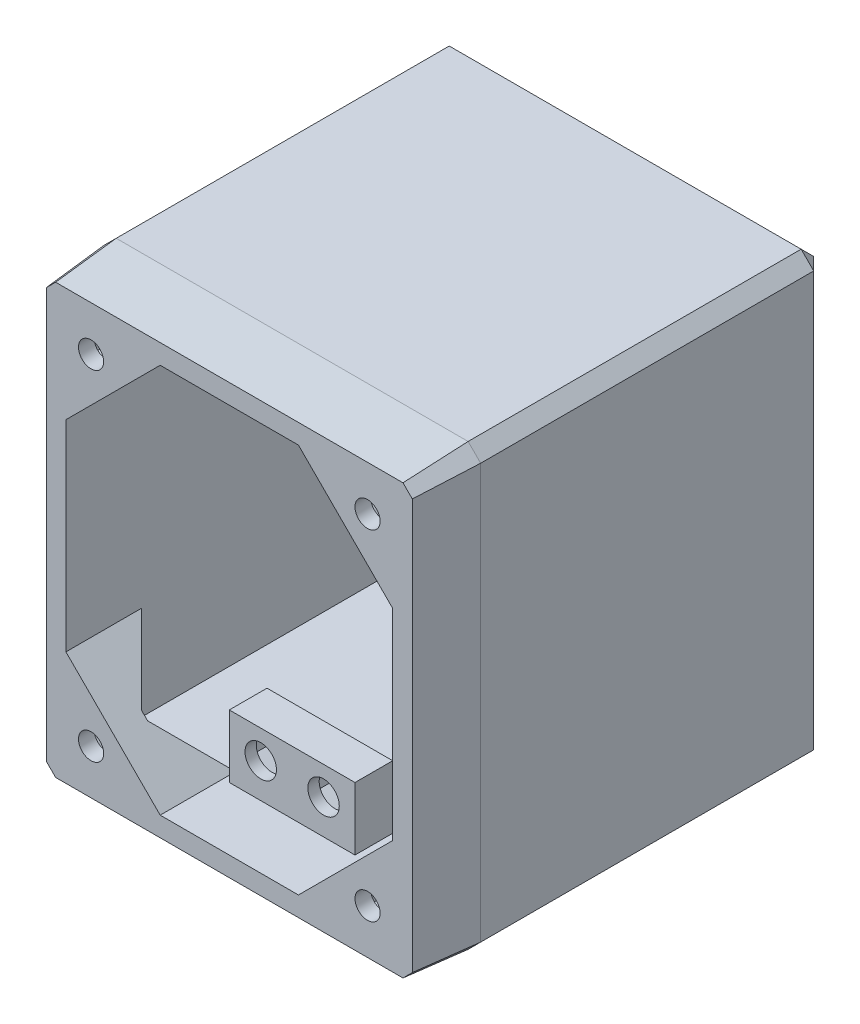
SolidWorks part; units mm, degrees
ref_plane "Ebene vorne" through (0, 0, 0) normal (0, 0, 1) x (1, 0, 0)
ref_plane "Ebene oben" through (0, 0, 0) normal (0, 1, 0) x (1, 0, 0)
ref_plane "Ebene rechts" through (0, 0, 0) normal (1, 0, 0) x (0, 0, -1)
sketch "Skizze1" plane through (0, 0, 0) normal (0, 0, 1) x (1, 0, 0)
  line L1 (0, 0) -> (60, 0)
  line L2 (0, 0) -> (0, 70)
  line L3 (0, 70) -> (60, 70)
  line L4 (60, 0) -> (60, 70)
  dimension "D1" = 60
  dimension "D2" = 70
extrude "Grundkörper" add sketch "Skizze1" along normal blind 65
chamfer "Fase2" distance 2 angle 45 7 edges at (0, 0, 32.5) (60, 0, 32.5) (60, 70, 32.5) (0, 70, 32.5) (0, 35, 0) (30, 70, 0) (60, 35, 0)
shell "Wandung1" thickness 4
sketch "Skizze2" plane through (0, 4, 0) normal (0, 1, 0) x (1, 0, 0)
  line L5 (30, -65) -> (30, -4) construction
  line L6 (4, -65) -> (56, -65) construction
  line L7 (4, -4) -> (56, -4) construction
  line L12 (40, -55) -> (20, -55)
  line L13 (20, -55) -> (20, -49)
  line L14 (20, -49) -> (40, -49)
  line L15 (58, -65) -> (2, -65) construction
  line L16 (40, -55) -> (40, -49)
  point P13 (30, -49)
  point P14 (30, -55)
  dimension "D1" = 10
  dimension "D2" = 6
  dimension "D3" = 20
extrude "Aufsatz-Linear austragen1" add sketch "Skizze2" along normal blind 10 contours L14 L16 L12 L13
ref_plane "Ebene1" through (0, 35, 0) normal (0, -1, 0) x (-1, 0, 0)
mirror "Spiegeln1" about plane through (0, 35, 0) normal (0, -1, 0) of "Aufsatz-Linear austragen1"
sketch "Skizze3" plane through (0, 0, 55) normal (0, 0, 1) x (1, 0, 0)
  line L0 (40, 14) -> (40, 4) construction
  line L2 (40, 4) -> (20, 4) construction
  line L3 (4, 4) -> (56, 4) construction
  line L4 (-28.6825, 35) -> (28.6825, 35) construction
  circle A0 centre (25, 9.5) radius 2.5
  circle A1 centre (35, 9.5) radius 2.5
  circle A2 centre (35, 60.5) radius 2.5
  circle A3 centre (25, 60.5) radius 2.5
  dimension "D3" = 5
  dimension "D4" = 5
  dimension "D1" = 10
  dimension "D2" = 5
  dimension "D5" = 5.5
  dimension "D6" = 5.5
extrude "Bohrungen Servo" cut sketch "Skizze3" against normal up to next
sketch "Skizze5" plane through (0, 0, 49) normal (0, 0, -1) x (-1, 0, 0)
  line L0 (-28.6825, 35) -> (28.6825, 35) construction
  line L1 (-34.9751, 13.5414) -> (-38.4875, 11.5423)
  line L2 (-38.4875, 11.5423) -> (-38.5124, 7.5009)
  line L3 (-38.5124, 7.5009) -> (-35.0249, 5.4586)
  line L4 (-35.0249, 5.4586) -> (-31.5125, 7.4577)
  line L5 (-31.5125, 7.4577) -> (-31.4876, 11.4991)
  line L6 (-31.4876, 11.4991) -> (-34.9751, 13.5414)
  line L7 (-31.4876, 58.5009) -> (-34.9751, 56.4586)
  line L8 (-31.5125, 62.5423) -> (-31.4876, 58.5009)
  line L9 (-35.0249, 64.5414) -> (-31.5125, 62.5423)
  line L10 (-38.5124, 62.4991) -> (-35.0249, 64.5414)
  line L11 (-38.4875, 58.4577) -> (-38.5124, 62.4991)
  line L12 (-34.9751, 56.4586) -> (-38.4875, 58.4577)
  line L13 (-30, 0) -> (-30, 70) construction
  line L14 (-2, 0) -> (-58, 0) construction
  line L15 (-58, 70) -> (-2, 70) construction
  line L16 (-28.4875, 62.5423) -> (-28.5124, 58.5009)
  line L17 (-24.9751, 64.5414) -> (-28.4875, 62.5423)
  line L18 (-21.4876, 62.4991) -> (-24.9751, 64.5414)
  line L19 (-21.5125, 58.4577) -> (-21.4876, 62.4991)
  line L20 (-25.0249, 56.4586) -> (-21.5125, 58.4577)
  line L21 (-28.5124, 58.5009) -> (-25.0249, 56.4586)
  line L22 (-28.5124, 11.4991) -> (-25.0249, 13.5414)
  line L23 (-25.0249, 13.5414) -> (-21.5125, 11.5423)
  line L24 (-21.5125, 11.5423) -> (-21.4876, 7.5009)
  line L25 (-21.4876, 7.5009) -> (-24.9751, 5.4586)
  line L26 (-24.9751, 5.4586) -> (-28.4875, 7.4577)
  line L27 (-28.4875, 7.4577) -> (-28.5124, 11.4991)
  circle A0 centre (-35, 9.5) radius 3.5 construction
  circle A1 centre (-35, 9.5) radius 2.5
  circle A2 centre (-25, 9.5) radius 2
  circle A3 centre (-25, 60.5) radius 2.5
  circle A4 centre (-35, 60.5) radius 2.5
  dimension "D2" = 4
  dimension "D1" = 7
extrude "Sechskant" cut sketch "Skizze5" against normal blind 4.2
sketch "Skizze7" plane through (0, 0, 65) normal (0, 0, 1) x (1, 0, 0)
  line L0 (56, 4) -> (41, 4)
  line L1 (4, 4) -> (56, 4) construction
  line L2 (41, 4) -> (56, 19)
  line L3 (56, 4) -> (56, 66) construction
  line L4 (56, 19) -> (56, 4)
  line L5 (30, 4) -> (30, 66) construction
  line L6 (40, 4) -> (20, 4) construction
  line L7 (56, 66) -> (4, 66) construction
  line L8 (19, 4) -> (4, 19)
  line L9 (4, 4) -> (19, 4)
  line L10 (4, 19) -> (4, 4)
  line L11 (-28.6825, 35) -> (28.6825, 35) construction
  line L12 (4, 66) -> (19, 66)
  line L13 (4, 51) -> (4, 66)
  line L14 (19, 66) -> (4, 51)
  line L15 (41, 66) -> (56, 51)
  line L16 (56, 66) -> (41, 66)
  line L17 (56, 51) -> (56, 66)
  dimension "D1" = 15
  dimension "D2" = 15
extrude "Ausparungen" add sketch "Skizze7" against normal blind 5
chamfer "Fase3" distance 7 angle 45 8 edges at (56, 58.5, 60) (48.5, 66, 60) (56, 11.5, 60) (48.5, 4, 60) (11.5, 66, 60) (4, 58.5, 60) (11.5, 4, 60) (4, 11.5, 60)
sketch "Skizze8" plane through (0, 0, 65) normal (0, 0, 1) x (1, 0, 0)
  line L0 (58, 0) -> (58, 70) construction
  line L1 (60, 2) -> (0, 2) construction
  line L2 (0, 2) -> (2, 0) construction
  line L3 (2, 0) -> (2, 70) construction
  line L4 (30, 0) -> (30, 70) construction
  line L5 (2, 0) -> (58, 0) construction
  line L6 (58, 70) -> (2, 70) construction
  line L7 (-28.6825, 35) -> (28.6825, 35) construction
  circle A0 centre (52, 8) radius 2
  circle A1 centre (8, 8) radius 2
  circle A2 centre (8, 62) radius 2
  circle A3 centre (52, 62) radius 2
  dimension "D1" = 4
  dimension "D2" = 6
  dimension "D3" = 6
extrude "BohrungenHalterung" cut sketch "Skizze8" against normal up to next
ref_plane "Ebene2" through (0, 0, 62.5) normal (0, 0, 1) x (1, 0, 0)
sketch "Skizze13" plane through (0, 0, 62.5) normal (0, 0, 1) x (1, 0, 0)
  line L0 (41, 66) -> (56, 51) construction
  line L1 (50.9092, 57.929) -> (54.9802, 59.0198)
  line L2 (54.9802, 59.0198) -> (56.071, 63.0908)
  line L3 (56.071, 63.0908) -> (53.0908, 66.071)
  line L4 (53.0908, 66.071) -> (49.0198, 64.9802)
  line L5 (49.0198, 64.9802) -> (47.929, 60.9092)
  line L6 (47.929, 60.9092) -> (50.9092, 57.929)
  line L7 (49.0198, 5.0198) -> (53.0908, 3.929)
  line L8 (53.0908, 3.929) -> (56.071, 6.9092)
  line L9 (56.071, 6.9092) -> (54.9802, 10.9802)
  line L10 (54.9802, 10.9802) -> (50.9092, 12.071)
  line L11 (50.9092, 12.071) -> (47.929, 9.0908)
  line L12 (47.929, 9.0908) -> (49.0198, 5.0198)
  line L13 (3.929, 6.9092) -> (6.9092, 3.929)
  line L14 (6.9092, 3.929) -> (10.9802, 5.0198)
  line L15 (10.9802, 5.0198) -> (12.071, 9.0908)
  line L16 (12.071, 9.0908) -> (9.0908, 12.071)
  line L17 (9.0908, 12.071) -> (5.0198, 10.9802)
  line L18 (5.0198, 10.9802) -> (3.929, 6.9092)
  line L19 (5.0198, 59.0198) -> (9.0908, 57.929)
  line L20 (9.0908, 57.929) -> (12.071, 60.9092)
  line L21 (12.071, 60.9092) -> (10.9802, 64.9802)
  line L22 (10.9802, 64.9802) -> (6.9092, 66.071)
  line L23 (6.9092, 66.071) -> (3.929, 63.0908)
  line L24 (3.929, 63.0908) -> (5.0198, 59.0198)
  line L25 (56, 19) -> (41, 4) construction
  line L26 (19, 4) -> (4, 19) construction
  line L27 (4, 51) -> (19, 66) construction
  circle A0 centre (52, 62) radius 3.65 construction
  circle A1 centre (52, 8) radius 3.65 construction
  circle A2 centre (8, 8) radius 3.65 construction
  circle A3 centre (8, 62) radius 3.65 construction
  dimension "D1" = 7.3
extrude "Sechskant Deckel" cut sketch "Skizze13" against normal up to vertex (7.4 mm away)
sketch "Skizze11" plane through (0, 0, 0) normal (0, 0, -1) x (-1, 0, 0)
  line L3 (-2, 68) -> (-58, 68) construction
  circle A1 centre (-30, 53) radius 3
  point P6 (0, 0)
  point P8 (-101.7684, 97.9938)
  dimension "D4" = 6
  dimension "D1" = 15
extrude "Bohrung Verschraubung Deckel" cut sketch "Skizze11" against normal up to next
sketch "Skizze14" plane through (0, 0, 0) normal (0, 0, -1) x (-1, 0, 0)
  line L5 (-36, 38) -> (-24, 38)
  line L6 (-36, 38) -> (-36, 48)
  line L7 (-36, 48) -> (-24, 48)
  line L8 (-24, 38) -> (-24, 48)
  line L9 (-36, 38) -> (-24, 48) construction
  line L10 (-36, 48) -> (-24, 38) construction
  circle A0 centre (-30, 53) radius 0.8839
  point P0 (-30, 43)
  dimension "D1" = 12
  dimension "D2" = 10
  dimension "D3" = 10
  dimension "D4" = 0
extrude "Vertiefung Deckel" cut sketch "Skizze14" against normal blind 2
sketch "Skizze16" plane through (0, 0, 0) normal (0, -1, 0) x (1, 0, 0)
  line L0 (0, 0) -> (0, 65) construction
  line L1 (0, 65) -> (60, 65) construction
  line L2 (60, 65) -> (60, 0) construction
  line L3 (60, 0) -> (0, 0) construction
  line L4 (0, 0) -> (30, 0) construction
  line L5 (30, 0) -> (30, 65) construction
  circle A0 centre (30, 20) radius 6.25
  dimension "D2" = 12.5
  dimension "D1" = 45
extrude "Aufsatz Kabelbohrungen" add sketch "Skizze16" along normal blind 4
sketch "Skizze17" plane through (0, -4, 0) normal (0, -1, 0) x (1, 0, 0)
  circle A0 centre (30, 20) radius 4.5
  dimension "D1" = 9
extrude "Bohrungsdurchmesser Kabel " cut sketch "Skizze17" against normal up to next
chamfer "Fase4" distance 10 angle 5 8 edges at (60, 35, 65) (59, 1, 65) (30, 0, 65) (1, 1, 65) (0, 35, 65) (1, 69, 65) (30, 70, 65) (59, 69, 65)
